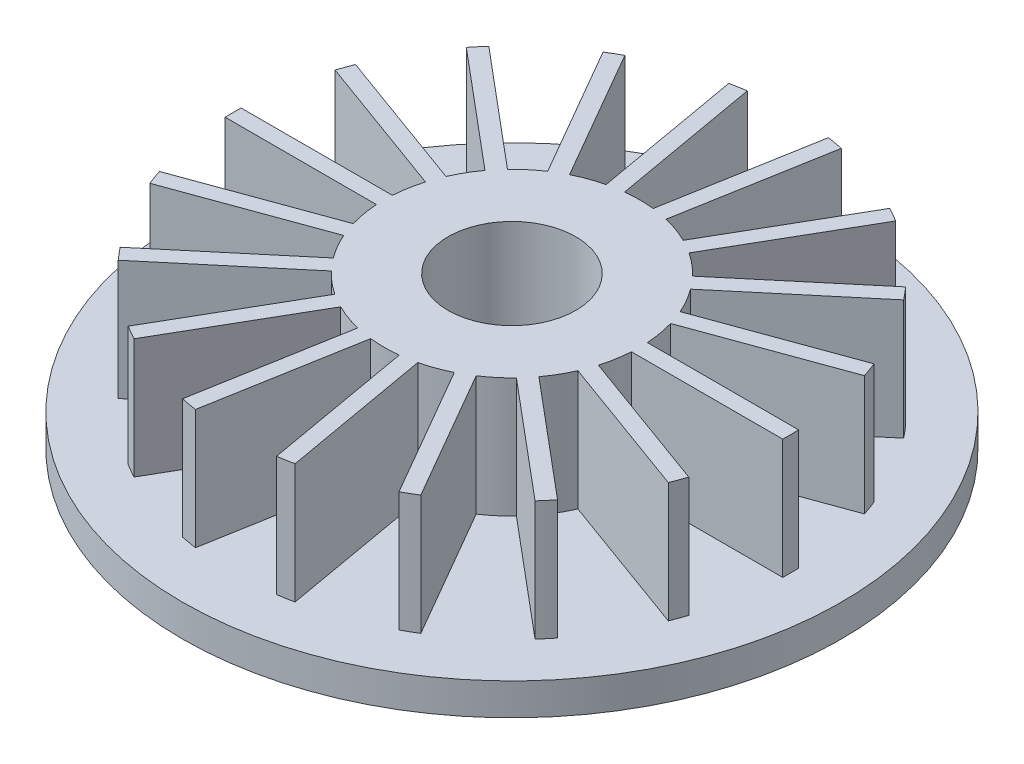
SolidWorks part; units mm, degrees
ref_plane "Front Plane" through (0, 0, 0) normal (0, 0, 1) x (1, 0, 0)
ref_plane "Top Plane" through (0, 0, 0) normal (0, 1, 0) x (1, 0, 0)
ref_plane "Right Plane" through (0, 0, 0) normal (1, 0, 0) x (0, 0, -1)
sketch "Sketch1" plane through (0, 0, 0) normal (0, 1, 0) x (1, 0, 0)
  circle A0 centre (0, 0) radius 8
  dimension "D1" = 16
extrude "Boss-Extrude1" add sketch "Sketch1" along normal blind 7.5
sketch "Sketch3" plane through (0, 0, 0) normal (1, 0, 0) x (0, 0, -1)
  line L0 (0, 0) -> (0, 12.831) construction
sketch "Sketch2" plane through (0, 0, 0) normal (0, -1, 0) x (1, 0, 0)
  line L0 (29.4625, 0.5) -> (5.4625, 0.5)
  line L1 (29.4625, 0.5) -> (29.4625, -0.5)
  line L2 (5.4625, 0.5) -> (5.4625, -0.5)
  line L3 (29.4625, -0.5) -> (5.4625, -0.5)
  line L4 (29.4625, 0.5) -> (5.4625, -0.5) construction
  line L5 (5.4625, 0.5) -> (29.4625, -0.5) construction
  line L6 (27.5147, -10.5466) -> (4.9621, -2.3381)
  line L7 (27.8567, -9.6069) -> (27.5147, -10.5466)
  line L8 (27.8567, -9.6069) -> (5.3041, -1.3984)
  line L9 (5.3041, -1.3984) -> (4.9621, -2.3381)
  line L10 (22.2482, -19.3212) -> (3.8631, -3.8942)
  line L11 (22.891, -18.5551) -> (22.2482, -19.3212)
  line L12 (22.891, -18.5551) -> (4.5059, -3.1282)
  line L13 (4.5059, -3.1282) -> (3.8631, -3.8942)
  line L14 (14.2982, -25.7653) -> (2.2982, -4.9807)
  line L15 (15.1643, -25.2653) -> (14.2982, -25.7653)
  line L16 (15.1643, -25.2653) -> (3.1643, -4.4807)
  line L17 (3.1643, -4.4807) -> (2.2982, -4.9807)
  line L18 (4.6237, -29.1017) -> (0.4561, -5.4663)
  line L19 (5.6085, -28.9281) -> (4.6237, -29.1017)
  line L20 (5.6085, -28.9281) -> (1.441, -5.2927)
  line L21 (1.441, -5.2927) -> (0.4561, -5.4663)
  line L22 (-5.6085, -28.9281) -> (-1.441, -5.2927)
  line L23 (-4.6237, -29.1017) -> (-5.6085, -28.9281)
  line L24 (-4.6237, -29.1017) -> (-0.4561, -5.4663)
  line L25 (-0.4561, -5.4663) -> (-1.441, -5.2927)
  line L26 (-15.1643, -25.2653) -> (-3.1643, -4.4807)
  line L27 (-14.2982, -25.7653) -> (-15.1643, -25.2653)
  line L28 (-14.2982, -25.7653) -> (-2.2982, -4.9807)
  line L29 (-2.2982, -4.9807) -> (-3.1643, -4.4807)
  line L30 (-22.891, -18.5551) -> (-4.5059, -3.1282)
  line L31 (-22.2482, -19.3212) -> (-22.891, -18.5551)
  line L32 (-22.2482, -19.3212) -> (-3.8631, -3.8942)
  line L33 (-3.8631, -3.8942) -> (-4.5059, -3.1282)
  line L34 (-27.8567, -9.6069) -> (-5.3041, -1.3984)
  line L35 (-27.5147, -10.5466) -> (-27.8567, -9.6069)
  line L36 (-27.5147, -10.5466) -> (-4.9621, -2.3381)
  line L37 (-4.9621, -2.3381) -> (-5.3041, -1.3984)
  line L38 (-29.4625, 0.5) -> (-5.4625, 0.5)
  line L39 (-29.4625, -0.5) -> (-29.4625, 0.5)
  line L40 (-29.4625, -0.5) -> (-5.4625, -0.5)
  line L41 (-5.4625, -0.5) -> (-5.4625, 0.5)
  line L42 (-27.5147, 10.5466) -> (-4.9621, 2.3381)
  line L43 (-27.8567, 9.6069) -> (-27.5147, 10.5466)
  line L44 (-27.8567, 9.6069) -> (-5.3041, 1.3984)
  line L45 (-5.3041, 1.3984) -> (-4.9621, 2.3381)
  line L46 (-22.2482, 19.3212) -> (-3.8631, 3.8942)
  line L47 (-22.891, 18.5551) -> (-22.2482, 19.3212)
  line L48 (-22.891, 18.5551) -> (-4.5059, 3.1282)
  line L49 (-4.5059, 3.1282) -> (-3.8631, 3.8942)
  line L98 (-14.2982, 25.7653) -> (-2.2982, 4.9807)
  line L99 (-15.1643, 25.2653) -> (-14.2982, 25.7653)
  line L100 (-15.1643, 25.2653) -> (-3.1643, 4.4807)
  line L101 (-3.1643, 4.4807) -> (-2.2982, 4.9807)
  line L102 (-4.6237, 29.1017) -> (-0.4561, 5.4663)
  line L103 (-5.6085, 28.9281) -> (-4.6237, 29.1017)
  line L104 (-5.6085, 28.9281) -> (-1.441, 5.2927)
  line L105 (-1.441, 5.2927) -> (-0.4561, 5.4663)
  line L106 (5.6085, 28.9281) -> (1.441, 5.2927)
  line L107 (4.6237, 29.1017) -> (5.6085, 28.9281)
  line L108 (4.6237, 29.1017) -> (0.4561, 5.4663)
  line L109 (0.4561, 5.4663) -> (1.441, 5.2927)
  line L110 (15.1643, 25.2653) -> (3.1643, 4.4807)
  line L111 (14.2982, 25.7653) -> (15.1643, 25.2653)
  line L112 (14.2982, 25.7653) -> (2.2982, 4.9807)
  line L113 (2.2982, 4.9807) -> (3.1643, 4.4807)
  line L114 (22.891, 18.5551) -> (4.5059, 3.1282)
  line L115 (22.2482, 19.3212) -> (22.891, 18.5551)
  line L116 (22.2482, 19.3212) -> (3.8631, 3.8942)
  line L117 (3.8631, 3.8942) -> (4.5059, 3.1282)
  line L118 (27.8567, 9.6069) -> (5.3041, 1.3984)
  line L119 (27.5147, 10.5466) -> (27.8567, 9.6069)
  line L120 (27.5147, 10.5466) -> (4.9621, 2.3381)
  line L121 (4.9621, 2.3381) -> (5.3041, 1.3984)
  line L122 (17.4625, 0) -> (0, 0) construction
  point P1 (17.4625, 0)
  point P100 (0, 0)
  dimension "D1" = 17.4625
  dimension "D2" = 24
  dimension "D3" = 1
  dimension "D4" = 18
extrude "Boss-Extrude2" add sketch "Sketch2" against normal up to surface (7.5 mm away) up to face at (0, 7.5, 8)
sketch "Sketch5" plane through (0, 0, 0) normal (1, 0, 0) x (0, 0, -1)
  line L0 (17.4625, 9) -> (47.4625, 9)
  line L1 (17.4625, 9) -> (17.4625, -1)
  line L2 (47.4625, 9) -> (47.4625, -1)
  line L3 (17.4625, -1) -> (47.4625, -1)
  dimension "D1" = 17.4625
  dimension "D2" = 30
  dimension "D3" = 10
  dimension "D4" = 1
revolve "Cut-Revolve1" cut sketch "Sketch5" angle 360 about L0
sketch "Sketch6" plane through (0, 0, 0) normal (0, 1, 0) x (1, 0, 0)
  circle A0 centre (0, 0) radius 20.6375
  dimension "D1" = 41.275
extrude "Boss-Extrude3" add sketch "Sketch6" against normal blind 2
sketch "Sketch7" plane through (0, 7.5, 0) normal (0, 1, 0) x (1, 0, 0)
  circle A0 centre (0, 0) radius 4
  dimension "D1" = 8
extrude "Cut-Extrude2" cut sketch "Sketch7" against normal through all contours A0
